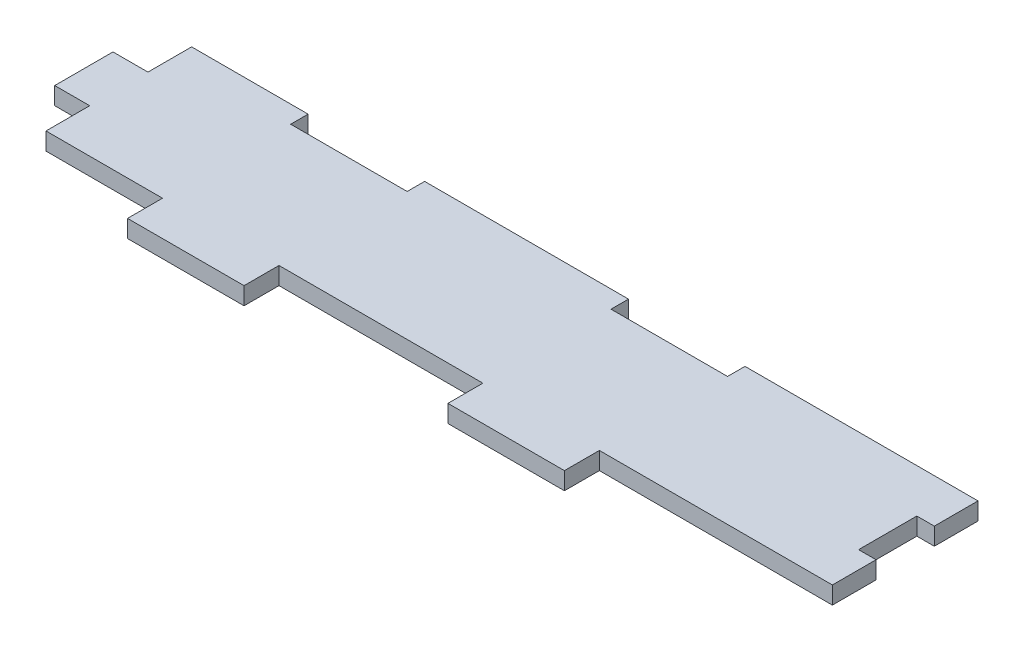
SolidWorks part; units mm, degrees
ref_plane "Спереди" through (0, 0, 0) normal (0, 0, 1) x (1, 0, 0)
ref_plane "Сверху" through (0, 0, 0) normal (0, 1, 0) x (1, 0, 0)
ref_plane "Справа" through (0, 0, 0) normal (1, 0, 0) x (0, 0, -1)
sketch "Эскиз1" plane through (0, 0, 0) normal (0, 1, 0) x (1, 0, 0)
  line L0 (135, 17.5) -> (135, 25)
  line L1 (0, 0) -> (20, 0)
  line L2 (0, 0) -> (0, 7.5)
  line L3 (0, 25) -> (20, 25)
  line L4 (135, 0) -> (135, 7.5)
  line L6 (20, 0) -> (20, -6)
  line L7 (20, -6) -> (40, -6)
  line L8 (40, 0) -> (40, -6)
  line L10 (75, 0) -> (75, -6)
  line L11 (75, -6) -> (95, -6)
  line L12 (95, 0) -> (95, -6)
  line L13 (135, 17.5) -> (132, 17.5)
  line L15 (135, 7.5) -> (132, 7.5)
  line L16 (132, 17.5) -> (132, 7.5)
  line L17 (0, 17.5) -> (-6, 17.5)
  line L19 (0, 7.5) -> (-6, 7.5)
  line L20 (-6, 17.5) -> (-6, 7.5)
  line L22 (20, 25) -> (20, 22)
  line L23 (20, 22) -> (40, 22)
  line L24 (40, 25) -> (40, 22)
  line L26 (75, 25) -> (75, 22)
  line L27 (75, 22) -> (95, 22)
  line L28 (95, 25) -> (95, 22)
  line L29 (95, 25) -> (135, 25)
  line L30 (95, 0) -> (135, 0)
  line L31 (40, 0) -> (75, 0)
  line L32 (40, 25) -> (75, 25)
  line L33 (0, 17.5) -> (0, 25)
  dimension "D1" = 135
  dimension "D2" = 25
  dimension "D3" = 3
  dimension "D4" = 6
  dimension "D5" = 6
  dimension "D6" = 3
  dimension "D7" = 10
  dimension "D8" = 7.5
  dimension "D9" = 20
  dimension "D10" = 20
  dimension "D11" = 35
  dimension "D12" = 20
  dimension "D13" = 37
extrude "Бобышка-Вытянуть1" add sketch "Эскиз1" along normal blind 3
